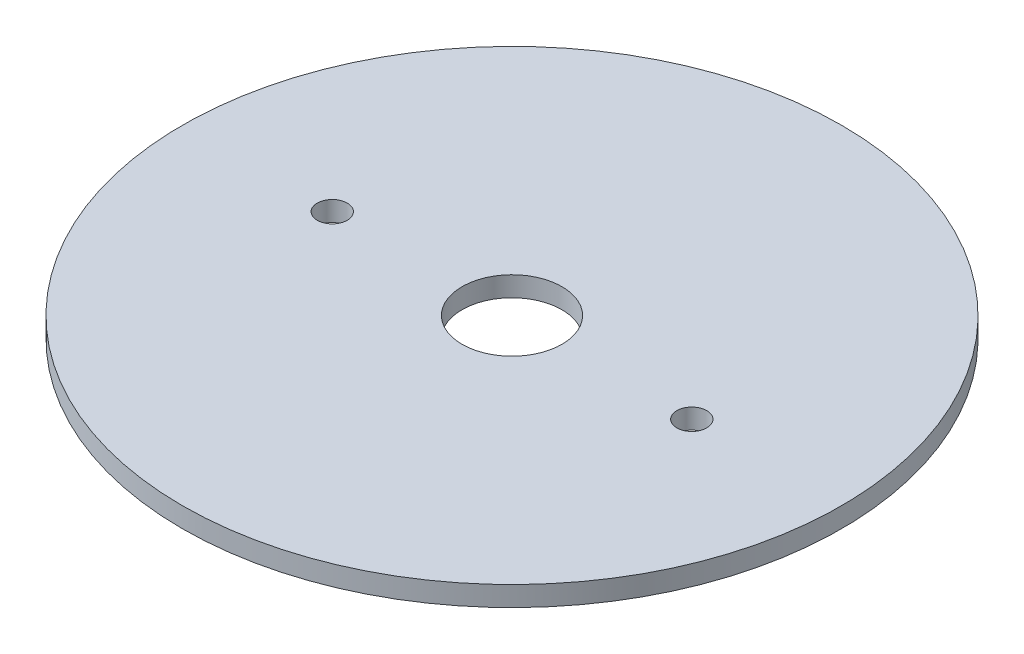
SolidWorks part; units mm, degrees
ref_plane "Front Plane" through (0, 0, 0) normal (0, 0, 1) x (1, 0, 0)
ref_plane "Top Plane" through (0, 0, 0) normal (0, 1, 0) x (1, 0, 0)
ref_plane "Right Plane" through (0, 0, 0) normal (1, 0, 0) x (0, 0, -1)
sketch "Sketch1" plane through (0, 0, 0) normal (0, 1, 0) x (1, 0, 0)
  line L0 (-33, 0) -> (33, 0) construction
  circle A0 centre (0, 0) radius 33
  circle A1 centre (0, 0) radius 5
  circle A2 centre (18, 0) radius 1.5
  circle A3 centre (-18, 0) radius 1.5
  point P5 (-18, 0)
  point P6 (18, 0)
  dimension "D1" = 66
  dimension "D2" = 10
  dimension "D3" = 3
  dimension "D4" = 3
  dimension "D5" = 18
  dimension "D6" = 18
extrude "Boss-Extrude2" add sketch "Sketch1" along normal blind 2
